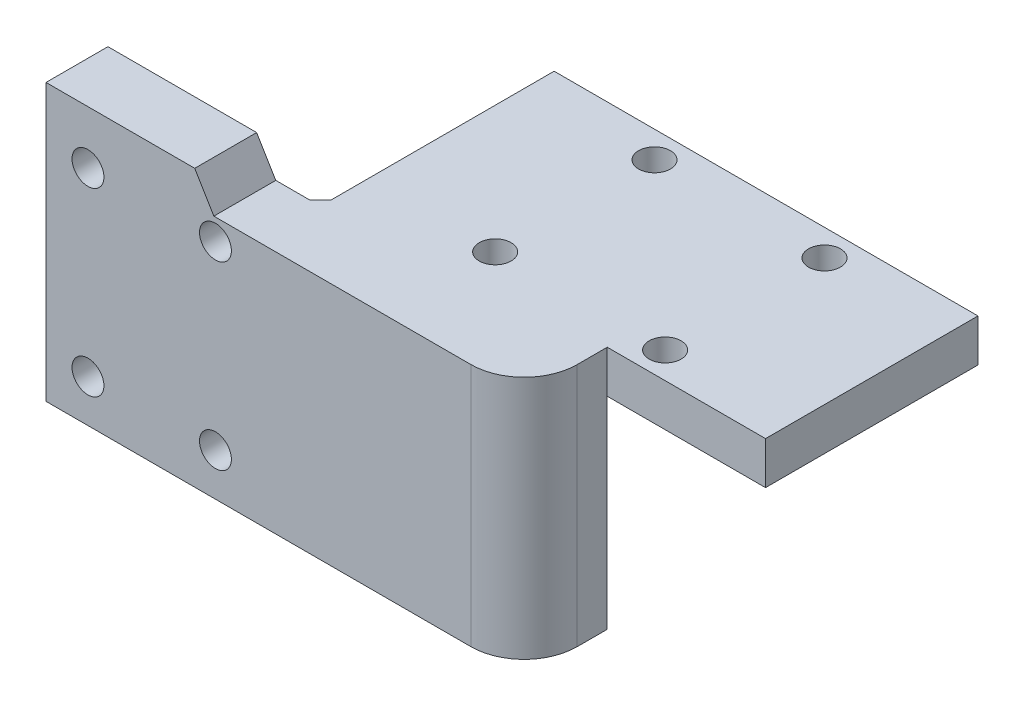
SolidWorks part; units mm, degrees
material "聚脂树脂"
ref_plane "前视基准面" through (0, 0, 0) normal (0, 0, 1) x (1, 0, 0)
ref_plane "上视基准面" through (0, 0, 0) normal (0, 1, 0) x (1, 0, 0)
ref_plane "右视基准面" through (0, 0, 0) normal (1, 0, 0) x (0, 0, -1)
other "Configuration Table"
sketch "草图1" plane through (0, 0, 0) normal (0, 1, 0) x (1, 0, 0)
  line L0 (0, 0) -> (26.53, 0) construction
  line L1 (-19.95, -10) -> (19.95, -10)
  line L2 (-19.95, -10) -> (-19.95, 10)
  line L3 (-19.95, 10) -> (19.95, 10)
  line L4 (19.95, -10) -> (19.95, 10)
  line L5 (-19.95, -10) -> (19.95, 10) construction
  line L6 (-19.95, 10) -> (19.95, -10) construction
  line L7 (0, 0) -> (0, 15.2425) construction
  circle A0 centre (8, 7.5) radius 1.5
  circle A1 centre (8, -7.5) radius 1.5
  circle A2 centre (-8, -7.5) radius 1.5
  circle A3 centre (-8, 7.5) radius 1.5
  point P0 (0, 0)
  dimension "D3" = 3
  dimension "D4" = 16
  dimension "D5" = 15
  dimension "D1" = 39.9
  dimension "D2" = 20
extrude "凸台-拉伸1" add sketch "草图1" along normal blind 4
sketch "草图6" plane through (-19.95, 0, 0) normal (-1, 0, 0) x (0, 0, 1)
  line L0 (-10, 4) -> (10, 4)
  line L1 (10, 4) -> (17.83, 4)
  line L2 (17.83, 4) -> (17.83, -19)
  line L3 (17.83, -19) -> (10, -19)
  line L4 (10, -19) -> (10, 0)
  line L5 (10, 0) -> (-10, 0)
  line L6 (-10, 0) -> (-10, 4)
  dimension "D1" = 7.83
  dimension "D2" = 23
extrude "凸台-拉伸4" add sketch "草图6" along normal blind 20
sketch "草图7" plane through (0, 0, 17.83) normal (0, 0, 1) x (1, 0, 0)
  line L0 (0, 0) -> (0, -15.8789) construction
  line L2 (-19.95, 0) -> (19.95, 0) construction
  circle A0 centre (-36, 2) radius 1.5
  circle A1 centre (-24, 2) radius 1.5
  circle A2 centre (-36, -15) radius 1.5
  circle A3 centre (-24, -15) radius 1.5
  dimension "D1" = 3
  dimension "D2" = 3
  dimension "D3" = 3
  dimension "D4" = 3
  dimension "D5" = 12
  dimension "D6" = 12
  dimension "D7" = 17
  dimension "D8" = 17
  dimension "D10" = 2
  dimension "D12" = 24
  dimension "D9" = 2
  dimension "D11" = 24
extrude "切除-拉伸3" cut sketch "草图7" against normal blind 15
sketch "草图8" plane through (0, 0, 10) normal (0, 0, 1) x (1, 0, 0)
  line L0 (-19.95, 4) -> (5.05, 4)
  line L1 (-19.95, 4) -> (19.95, 4) construction
  line L2 (-19.95, 4) -> (-19.95, -19)
  line L3 (-19.95, -19) -> (5.05, -19)
  line L4 (5.05, -19) -> (5.05, 4)
  dimension "D1" = 25
extrude "凸台-拉伸5" add sketch "草图8" along normal up to surface (7.83 mm away) up to face at (-22.5, 2, 17.83)
sketch "草图9" plane through (0, 0, -10) normal (0, 0, -1) x (-1, 0, 0)
  line L0 (39.95, 0) -> (39.95, 4)
  line L1 (39.95, 4) -> (19.95, 4)
  line L2 (-19.95, 4) -> (39.95, 4) construction
  line L3 (19.95, 4) -> (19.95, 0)
  line L4 (39.95, 0) -> (-5.05, 0) construction
  line L5 (19.95, 0) -> (39.95, 0)
  dimension "D1" = 20
extrude "切除-拉伸4" cut sketch "草图9" against normal blind 20
fillet "圆角1" radius 5 1 edges at (5.05, -7.5, 17.83)
sketch "草图12" plane through (0, 0, 10) normal (0, 0, -1) x (-1, 0, 0)
  line L0 (19.95, 4) -> (39.95, 4)
  line L1 (39.95, 4) -> (19.95, 4) construction
  line L2 (39.95, 4) -> (39.95, -19)
  line L3 (39.95, -19) -> (19.95, -19)
  line L4 (39.95, -19) -> (-5.05, -19) construction
  line L5 (19.95, -19) -> (19.95, 4)
  dimension "D1" = 20
extrude "切除-拉伸5" cut sketch "草图12" against normal blind 2
sketch "草图14" plane through (0, 4, 0) normal (0, 1, 0) x (1, 0, 0)
  line L0 (-19.95, -12) -> (-19.95, -17.83)
  line L1 (-39.95, -17.83) -> (0.05, -17.83) construction
  line L2 (-19.95, -17.83) -> (-39.95, -17.83)
  line L3 (-39.95, -17.83) -> (-39.95, -12)
  line L4 (-39.95, -12) -> (-19.95, -12)
extrude "凸台-拉伸6" add sketch "草图14" along normal blind 3
chamfer "倒角1" distance 1 angle 45 1 edges at (-19.95, -7.5, 12)
sketch "草图16" plane through (0, 0, 17.83) normal (0, 0, 1) x (1, 0, 0)
  line L0 (-19.95, 4) -> (-24.15, 4)
  line L1 (-24.15, 4) -> (-25.95, 7)
  line L2 (-39.95, 7) -> (-19.95, 7) construction
  line L3 (-25.95, 7) -> (-19.95, 7)
  line L4 (-19.95, 7) -> (-19.95, 4)
  dimension "D1" = 4.2
  dimension "D2" = 6
extrude "切除-拉伸6" cut sketch "草图16" against normal blind 10
